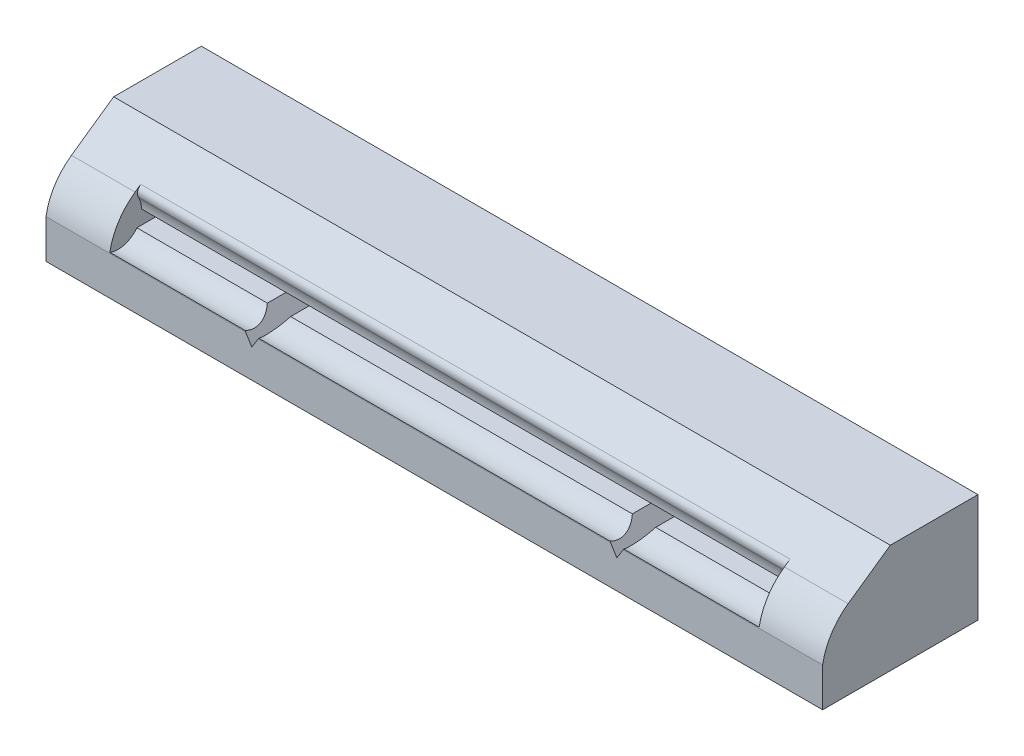
SolidWorks part; units mm, degrees
material "Сосна"
ref_plane "Front" through (0, 0, 0) normal (0, 0, 1) x (1, 0, 0)
ref_plane "Top" through (0, 0, 0) normal (0, 1, 0) x (1, 0, 0)
ref_plane "Right" through (0, 0, 0) normal (1, 0, 0) x (0, 0, -1)
sketch "Эскиз1" plane through (0, 66.7543, 0) normal (0, 0, 1) x (-1, 0, 0)
  line L1 (25, 63.2543) -> (-25, 70.2543) construction
  line L31 (-25, 63.2543) -> (25, 63.2543)
  line L32 (-25, 63.2543) -> (-25, 70.2543)
  line L33 (-25, 70.2543) -> (25, 70.2543)
  line L34 (25, 63.2543) -> (25, 70.2543)
  line L35 (-25, 63.2543) -> (25, 70.2543) construction
  point P12 (0, 66.7543)
  point P22 (0, 66.7543)
  point P26 (0, 66.7543)
  dimension "D1" = 7
  dimension "D2" = 50
extrude "Бобышка-Вытянуть1" add sketch "Эскиз1" along normal blind 10
sketch "Эскиз3" plane through (0, 0, 10) normal (0, 0, 1) x (1, 0, 0)
  line L0 (0, -3.5) -> (0, 3.5) construction
  line L1 (-25, -3.5) -> (25, -3.5) construction
  line L2 (25, 3.5) -> (-25, 3.5) construction
  point P6 (0, 0)
sketch "Эскиз4" plane through (0, 66.7543, 10) normal (0, 0, 1) x (-1, 0, 0)
  line L0 (0, 66.3043) -> (0, 67.2043) construction
  line L1 (-20.9, 67.2043) -> (-12.5, 67.2043)
  line L4 (-20.9, 67.2043) -> (-20.9, 66.3043)
  line L5 (-20.9, 66.3043) -> (20.9, 66.3043)
  line L6 (20.9, 67.2043) -> (20.9, 66.3043)
  line L7 (-20.9, 67.2043) -> (20.9, 66.3043) construction
  line L8 (-20.9, 66.3043) -> (20.9, 67.2043) construction
  line L22 (20.9, 67.2043) -> (-20.9, 67.2043) construction
  line L23 (-12.5, 67.2043) -> (-11.75, 68.4043)
  line L24 (-11.75, 68.4043) -> (-11, 67.2043)
  line L25 (-11, 67.2043) -> (11, 67.2043)
  line L26 (11, 67.2043) -> (11.75, 68.4043)
  line L27 (11.75, 68.4043) -> (12.5, 67.2043)
  line L28 (12.5, 67.2043) -> (20.9, 67.2043)
  point P2 (0, 67.2043)
  point P6 (0, 66.7543)
  point P11 (-1.7814, 65.8788)
  dimension "D1" = 41.8
  dimension "D2" = 0.9
  dimension "D3" = 1.5
  dimension "D5" = 1.2
  dimension "D6" = 23.5
extrude "Вырез-Вытянуть2" cut sketch "Эскиз4" against normal blind 7.5
chamfer "Фаска2" distance 0.6 angle 80 4 edges at (11.375, -1.05, 2.5) (12.125, -1.05, 2.5) (-12.125, -1.05, 2.5) (-11.375, -1.05, 2.5)
sketch "Эскиз5" plane through (0, 0, 0) normal (1, 0, 0) x (0, 0, -1)
  line L3 (-10, -1) -> (-10, 3.5)
  line L6 (-10, 3.5) -> (-5.6441, 3.5)
  line L7 (-5.6441, 3.5) -> (-8.3617, 1.5972)
  line L8 (-8.3617, 1.5972) -> (-10, 0.45) construction
  line L10 (-10, 3.5) -> (0, 3.5) construction
  line L11 (-10, -1.65) -> (-10, -0.45) construction
  line L12 (-10, -3.5) -> (-10, 3.5) construction
  arc A1 (-10, -1) -> (-8.3617, 1.5972) centre (-6.085, -1.6543) cw
  point P3 (-10, 0.6443)
  dimension "D2" = 35
  dimension "D1" = 2
  dimension "D3" = 1
extrude "Вырез упор крышки" cut sketch "Эскиз5" against normal through all both and the other way through all
sketch "Эскиз6" plane through (0, 0, 0) normal (1, 0, 0) x (0, 0, -1)
  line L0 (-8.0001, 1.8504) -> (-10.8327, -0.133)
  line L1 (-8.3617, 1.5972) -> (-5.6441, 3.5) construction
  circle A0 centre (-9.4506, 0.45) radius 1.5 construction
  arc A1 (-10.8327, -0.133) -> (-8.1476, 1.1931) centre (-9.4506, 0.45) ccw
  arc A2 (-8.0001, 1.8504) -> (-8.1476, 1.1931) centre (-7.7133, 1.4408) ccw
  dimension "D1" = 3
  dimension "D2" = 0.5
extrude "Вырез под кольцо петли" cut sketch "Эскиз6" against normal up to surface and the other way up to surface up to face at (-20.9, 0.0033, 6.0865) other way up to face at (20.9, 0.0033, 6.0865)
